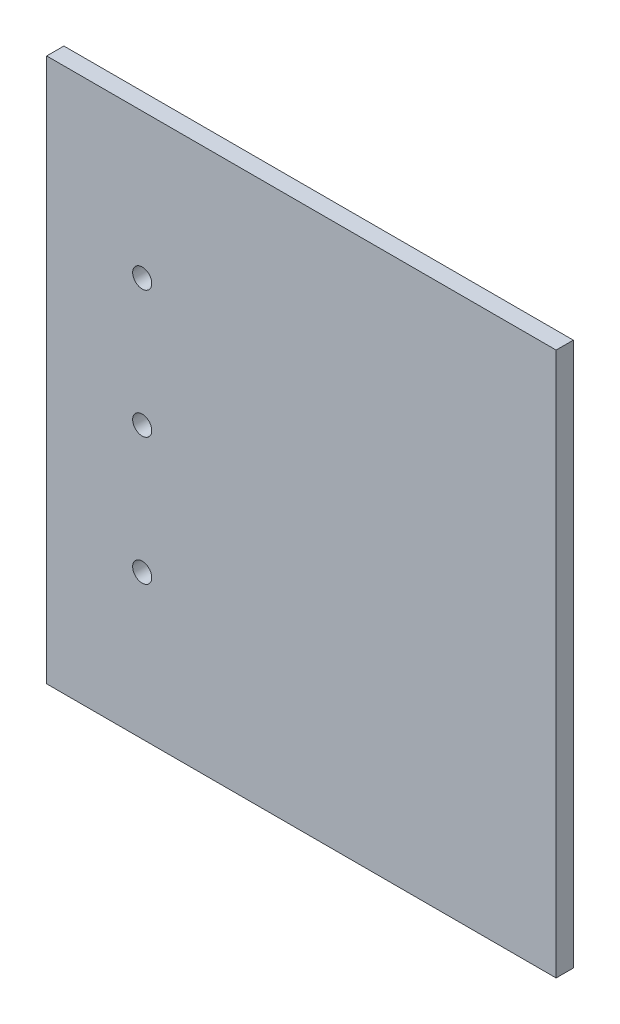
SolidWorks part; units mm, degrees
material "Acrílico (Impacto medio-alto)"
ref_plane "Alzado" through (0, 0, 0) normal (0, 0, 1) x (1, 0, 0)
ref_plane "Planta" through (0, 0, 0) normal (0, 1, 0) x (1, 0, 0)
ref_plane "Vista lateral" through (0, 0, 0) normal (1, 0, 0) x (0, 0, -1)
sketch "Croquis1" plane through (0, 0, 0) normal (0, 0, 1) x (1, 0, 0)
  line L1 (-82.7, 0) -> (-2.7, 0)
  line L2 (-82.7, 0) -> (-82.7, 85.4)
  line L3 (-82.7, 85.4) -> (-2.7, 85.4)
  line L4 (-2.7, 0) -> (-2.7, 85.4)
extrude "Saliente-Extruir1" add sketch "Croquis1" along normal blind 2.7
sketch "Croquis2" plane through (0, 0, 0) normal (0, 0, -1) x (-1, 0, 0)
  line L0 (42.7, 85.4) -> (42.7, 0) construction
  line L1 (2.7, 85.4) -> (82.7, 85.4) construction
  line L2 (82.7, 0) -> (2.7, 0) construction
  line L3 (82.7, 42.7) -> (42.7, 42.7) construction
  line L4 (82.7, 85.4) -> (82.7, 0) construction
  line L5 (67.7, 42.7) -> (67.7, 22.7) construction
  line L6 (67.7, 42.7) -> (67.7, 62.7) construction
  circle A0 centre (67.7, 42.7) radius 1.5
  circle A1 centre (67.7, 22.7) radius 1.5
  circle A2 centre (67.7, 62.7) radius 1.5
  dimension "D1" = 15
  dimension "D2" = 3
  dimension "D4" = 20
  dimension "D6" = 20
  dimension "D3" = 2
  dimension "D5" = 2
extrude "Cortar-Extruir1" cut sketch "Croquis2" against normal blind 2.7
